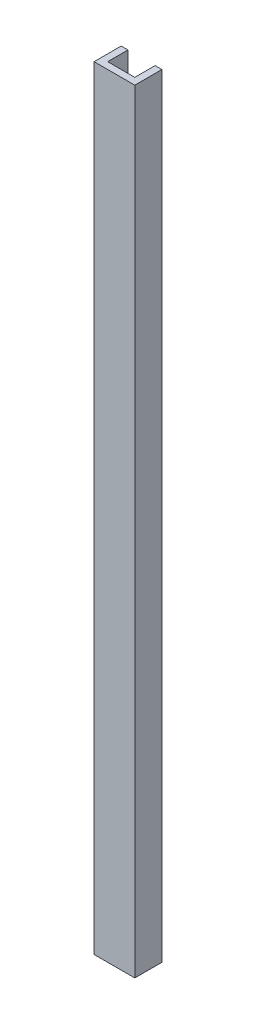
SolidWorks part; units mm, degrees
material "1060 Alloy"
ref_plane "Front Plane" through (0, 0, 0) normal (0, 0, 1) x (1, 0, 0)
ref_plane "Top Plane" through (0, 0, 0) normal (0, 1, 0) x (1, 0, 0)
ref_plane "Right Plane" through (0, 0, 0) normal (1, 0, 0) x (0, 0, -1)
sketch "Sketch1" plane through (0, 0, 0) normal (0, 1, 0) x (1, 0, 0)
  line L0 (0, 0) -> (19.05, 0)
  line L1 (19.05, 0) -> (19.05, 12.7)
  line L7 (0, 12.7) -> (0, 0)
  dimension "D1" = 12.7
  dimension "D2" = 19.05
  dimension "D3" = 12.7
extrude "Extrude-Thin1" add sketch "Sketch1" along normal blind 361.95 thin thin type one direction reverse wall 3.175
